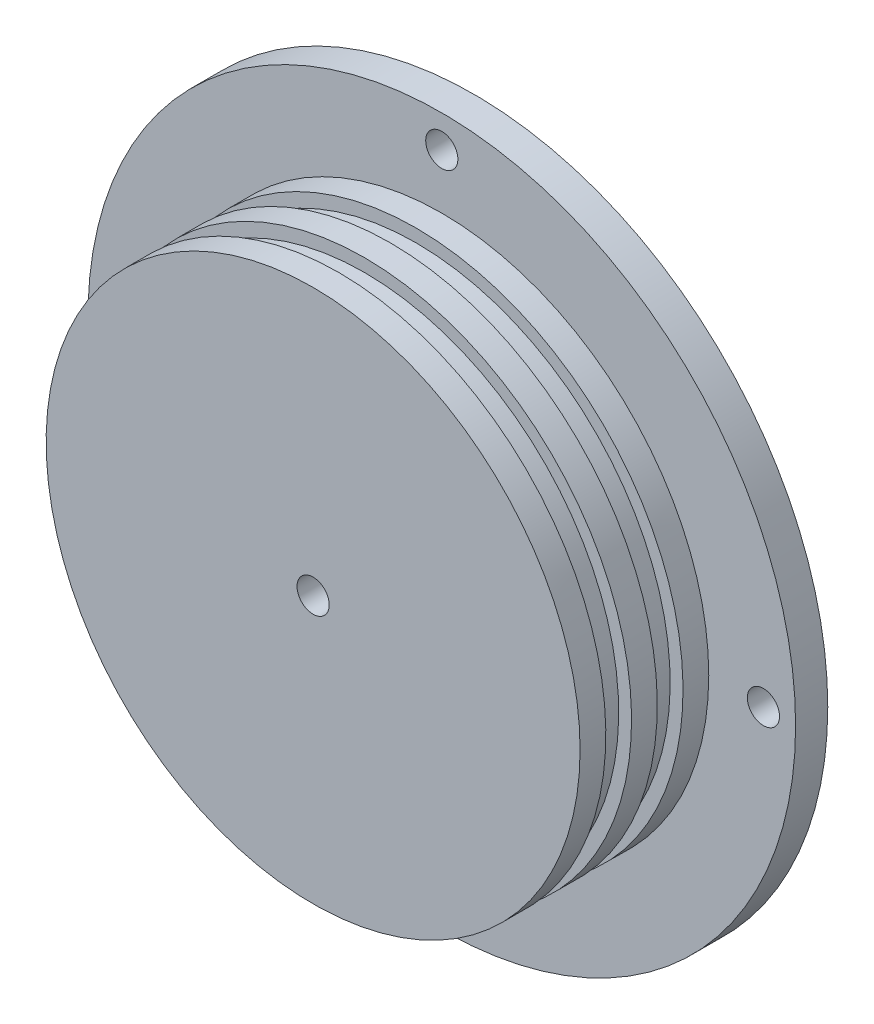
SolidWorks part; units mm, degrees
ref_plane "Front Plane" through (0, 0, 0) normal (0, 0, 1) x (1, 0, 0)
ref_plane "Top Plane" through (0, 0, 0) normal (0, 1, 0) x (1, 0, 0)
ref_plane "Right Plane" through (0, 0, 0) normal (1, 0, 0) x (0, 0, -1)
sketch "Sketch1" plane through (0, 0, 0) normal (0, 0, 1) x (1, 0, 0)
  circle A0 centre (0, 0) radius 55
  dimension "D1" = 110
extrude "Boss-Extrude1" add sketch "Sketch1" along normal blind 5
sketch "Sketch3" plane through (0, 0, 0) normal (0, 0, -1) x (-1, 0, 0)
  circle A0 centre (0, 50) radius 2.5
  dimension "D1" = 50
  dimension "D2" = 5
extrude "Cut-Extrude1" cut sketch "Sketch3" against normal through all
pattern_circular "CirPattern1" count 4 over 360 about axis through (0, 0, 0) along (0, 0, 1) of "Cut-Extrude1"
sketch "Sketch2" plane through (0, 0, 5) normal (0, 0, 1) x (1, 0, 0)
  circle A0 centre (0, 0) radius 41.5
  dimension "D1" = 83
extrude "Boss-Extrude2" add sketch "Sketch2" along normal blind 20
sketch "Sketch4" plane through (0, 0, 0) normal (1, 0, 0) x (0, 0, -1)
  line L0 (-5, 41.5) -> (-25, 41.5) construction
  line L5 (-13, 41.5) -> (-9, 41.5)
  line L6 (-13, 41.5) -> (-13, 39.5)
  line L7 (-13, 39.5) -> (-9, 39.5)
  line L8 (-9, 41.5) -> (-9, 39.5)
  line L9 (-21, 41.5) -> (-21, 39.5)
  line L10 (-5, 41.5) -> (-5, -41.5) construction
  line L11 (0, 0) -> (-33.7056, 0) construction
  line L12 (-21, 39.5) -> (-17, 39.5)
  line L13 (-17, 41.5) -> (-17, 39.5)
  line L14 (-21, 41.5) -> (-17, 41.5)
  point P8 (-9, 40.5)
  dimension "D1" = 4
  dimension "D2" = 4
  dimension "D3" = 2
  dimension "D4" = 4
revolve "Cut-Revolve1" cut sketch "Sketch4" angle 360 about L11
sketch "Sketch5" plane through (0, 0, 0) normal (0, 0, -1) x (-1, 0, 0)
  circle A0 centre (0, 0) radius 2.5
  dimension "D1" = 5
extrude "Cut-Extrude2" cut sketch "Sketch5" against normal through all
sketch "Sketch6" plane through (0, 0, 0) normal (0, 0, -1) x (-1, 0, 0)
  circle A0 centre (0, 0) radius 20
  dimension "D1" = 40
extrude "Cut-Extrude3" cut sketch "Sketch6" against normal blind 10
